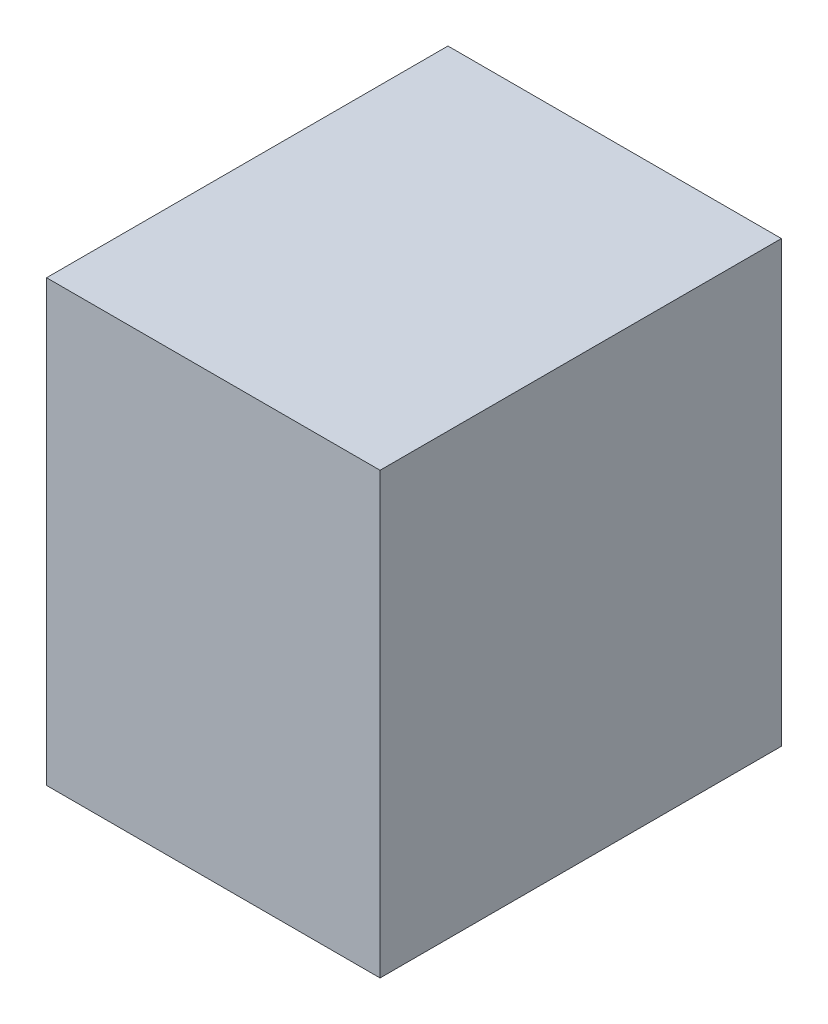
SolidWorks part; units mm, degrees
ref_plane "Front Plane" through (0, 0, 0) normal (0, 0, 1) x (1, 0, 0)
ref_plane "Top Plane" through (0, 0, 0) normal (0, 1, 0) x (1, 0, 0)
ref_plane "Right Plane" through (0, 0, 0) normal (1, 0, 0) x (0, 0, -1)
sketch "Sketch1" plane through (0, 0, 0) normal (0, 1, 0) x (1, 0, 0)
  line L1 (-56.5, 68) -> (56.5, 68)
  line L2 (-56.5, 68) -> (-56.5, -68)
  line L3 (-56.5, -68) -> (56.5, -68)
  line L4 (56.5, 68) -> (56.5, -68)
  line L5 (-56.5, 68) -> (56.5, -68) construction
  line L6 (-56.5, -68) -> (56.5, 68) construction
  point P0 (0, 0)
  dimension "D1" = 113
  dimension "D2" = 136
extrude "Boss-Extrude1" add sketch "Sketch1" along normal mid plane 149
